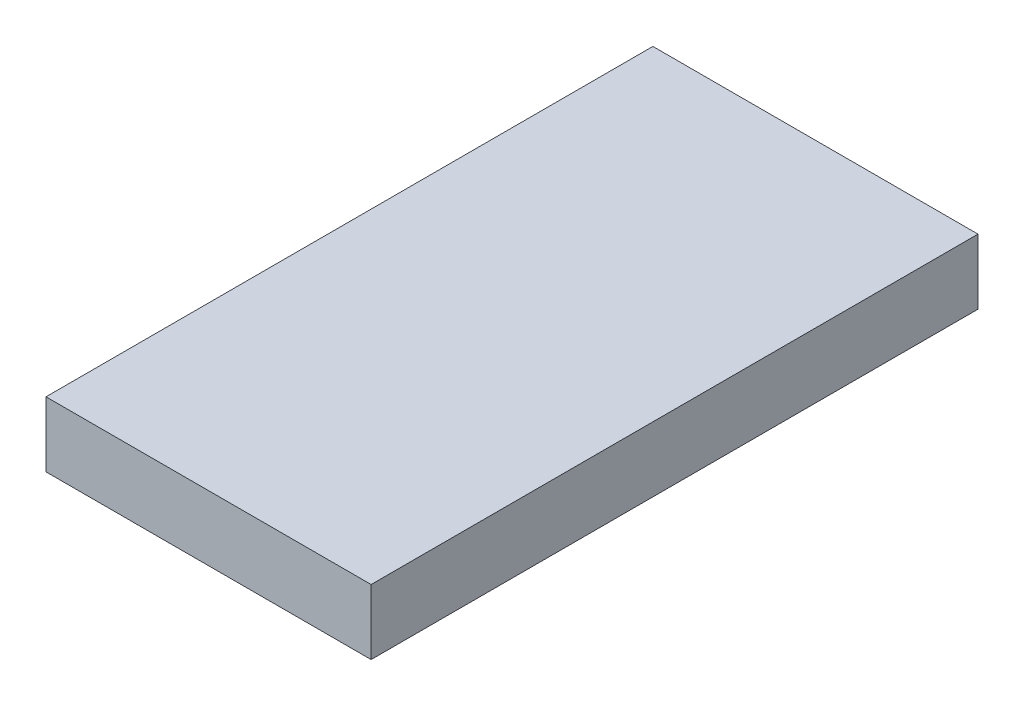
SolidWorks part; units mm, degrees
ref_plane "Plano frontal" through (0, 0, 0) normal (0, 0, 1) x (1, 0, 0)
ref_plane "Plano superior" through (0, 0, 0) normal (0, 1, 0) x (1, 0, 0)
ref_plane "Plano direito" through (0, 0, 0) normal (1, 0, 0) x (0, 0, -1)
sketch "PrendedorEsb" plane through (0, 0, 0) normal (0, 1, 0) x (1, 0, 0)
  line L1 (0, 0) -> (15, 0)
  line L2 (0, 0) -> (0, 28)
  line L3 (0, 28) -> (15, 28)
  line L4 (15, 0) -> (15, 28)
  dimension "D1" = 15
  dimension "D2" = 28
extrude "Trava" add sketch "PrendedorEsb" along normal blind 3
